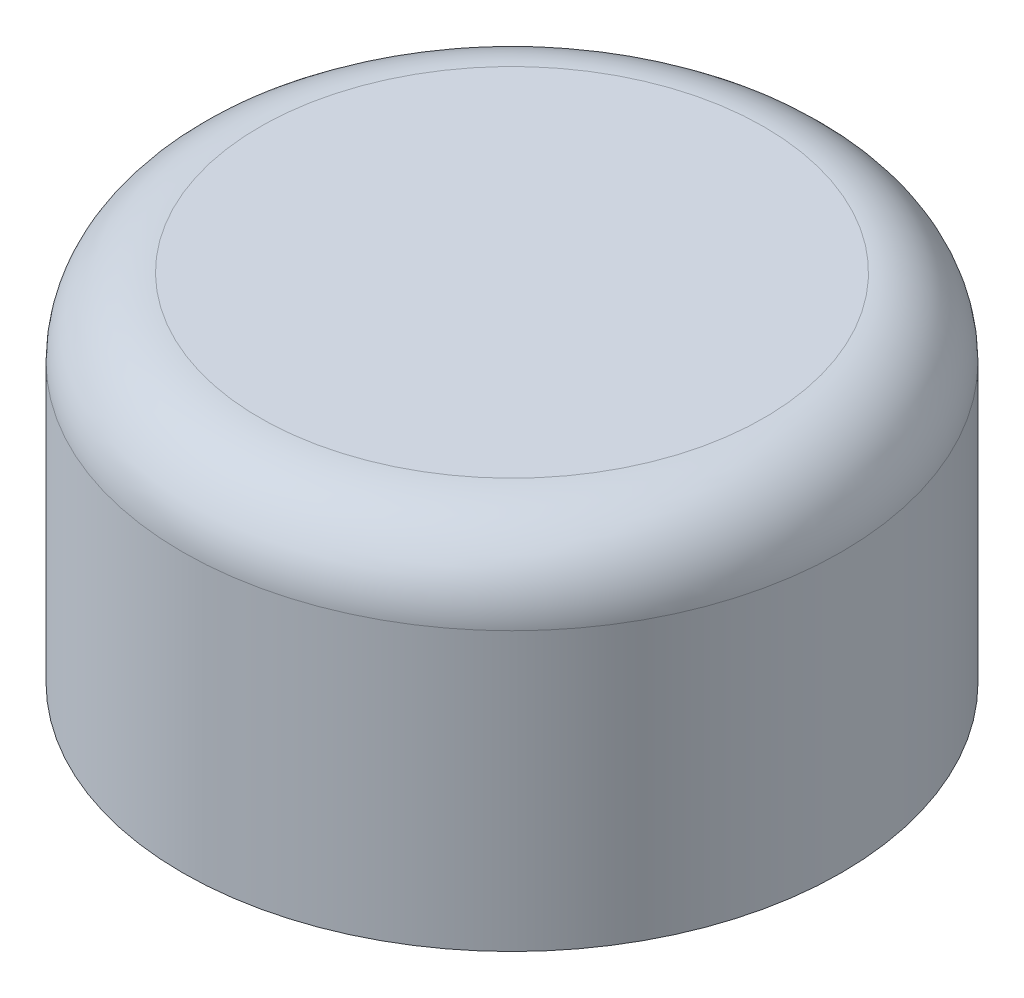
SolidWorks part; units mm, degrees
ref_plane "Front Plane" through (0, 0, 0) normal (0, 0, 1) x (1, 0, 0)
ref_plane "Top Plane" through (0, 0, 0) normal (0, 1, 0) x (1, 0, 0)
ref_plane "Right Plane" through (0, 0, 0) normal (1, 0, 0) x (0, 0, -1)
sketch "Sketch1" plane through (0, 0, 0) normal (0, 1, 0) x (1, 0, 0)
  circle A0 centre (0, 0) radius 37.85
  dimension "D1" = 75.7
extrude "Boss-Extrude1" add sketch "Sketch1" along normal blind 19.4
sketch "Sketch3" plane through (0, 0, 0) normal (1, 0, 0) x (0, 0, -1)
  line L0 (37.85, 19.4) -> (37.85, 30.8)
  line L1 (37.85, 30.8) -> (37.85, 31.91)
  line L2 (0, 19.4) -> (0, 40.8)
  line L3 (37.85, 19.4) -> (-37.85, 19.4) construction
  line L4 (28.96, 40.8) -> (0, 40.8)
  line L5 (37.85, 19.4) -> (0, 19.4)
  arc A0 (37.85, 31.91) -> (28.96, 40.8) centre (28.96, 31.91) ccw
  dimension "D3" = 8.89
  dimension "D1" = 11.4
  dimension "D2" = 21.4
revolve "Revolve1" add sketch "Sketch3" angle 360 about L2
sketch "Sketch4" plane through (0, 0, 0) normal (0, -1, 0) x (1, 0, 0)
  circle A1 centre (20.8597, 20.8597) radius 1.5
  circle A2 centre (-20.8597, 20.8597) radius 1.5
  circle A3 centre (-20.8597, -20.8597) radius 1.5
  circle A4 centre (20.8597, -20.8597) radius 1.5
  dimension "D2" = 3
  dimension "D3" = 3
  dimension "D4" = 3
  dimension "D5" = 3
extrude "Cut-Extrude1" cut sketch "Sketch4" against normal blind 1
